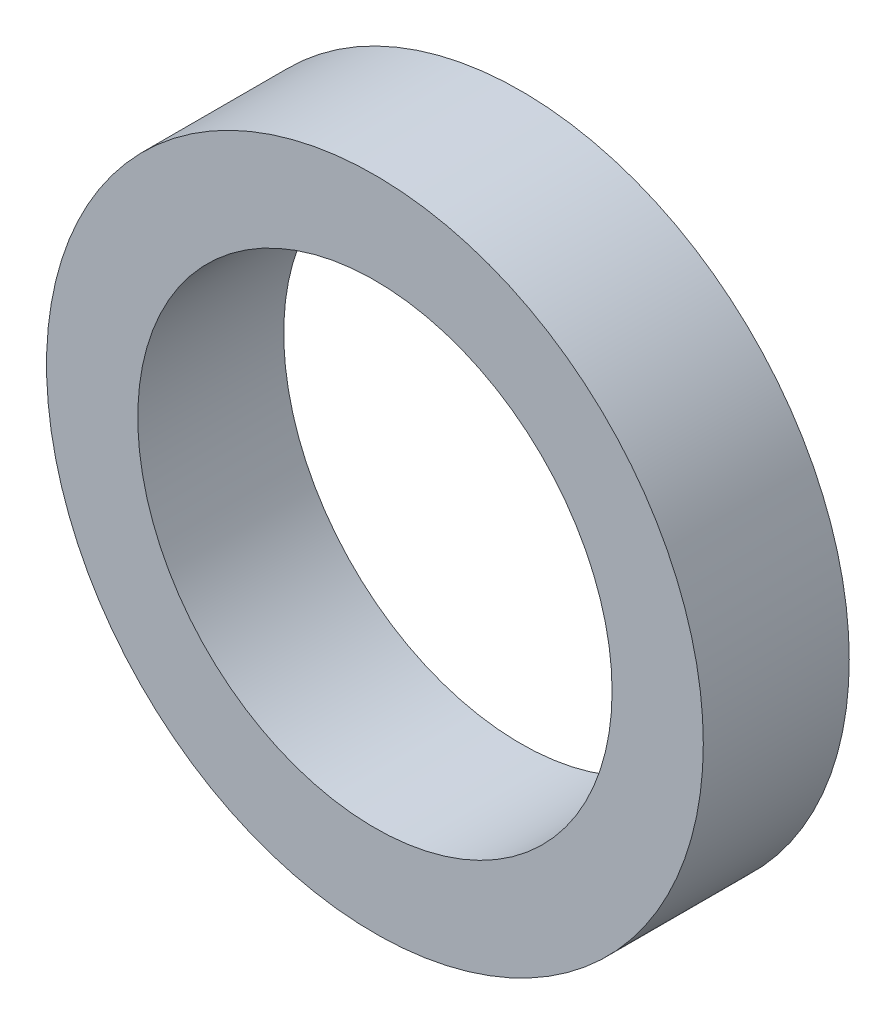
SolidWorks part; units mm, degrees
ref_plane "正面" through (0, 0, 0) normal (0, 0, 1) x (1, 0, 0)
ref_plane "平面" through (0, 0, 0) normal (0, 1, 0) x (1, 0, 0)
ref_plane "右側面" through (0, 0, 0) normal (1, 0, 0) x (0, 0, -1)
sketch "ｽｹｯﾁ1" plane through (0, 0, 0) normal (0, 0, 1) x (1, 0, 0)
  circle A0 centre (0, 0) radius 4.5
  circle A1 centre (0, 0) radius 3.25
  dimension "D1" = 6.5
  dimension "D2" = 9
extrude "ﾎﾞｽ - 押し出し1" add sketch "ｽｹｯﾁ1" along normal blind 2
